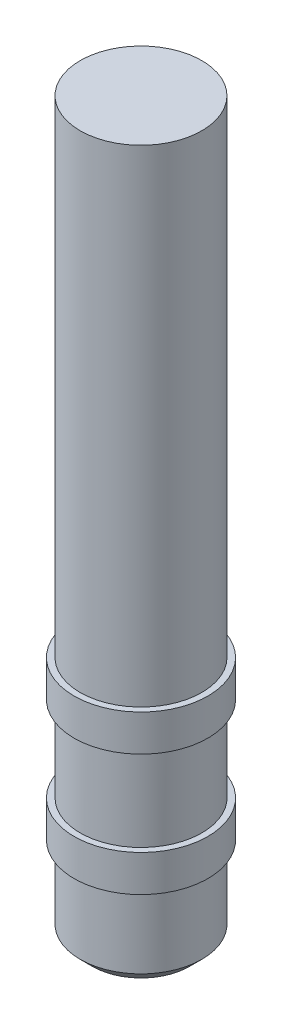
SolidWorks part; units mm, degrees
ref_plane "Front Plane" through (0, 0, 0) normal (0, 0, 1) x (1, 0, 0)
ref_plane "Top Plane" through (0, 0, 0) normal (0, 1, 0) x (1, 0, 0)
ref_plane "Right Plane" through (0, 0, 0) normal (1, 0, 0) x (0, 0, -1)
sketch "Sketch1" plane through (0, 0, 0) normal (0, 1, 0) x (1, 0, 0)
  circle A0 centre (0, 0) radius 5
  dimension "D1" = 10
extrude "Boss-Extrude1" add sketch "Sketch1" along normal blind 60
sketch "Sketch2" plane through (0, 60, 0) normal (0, 1, 0) x (1, 0, 0)
  circle A0 centre (0, 0) radius 5.5
  dimension "D1" = 11
extrude "Boss-Extrude2" add sketch "Sketch2" along normal blind 3 from offset 43 offset against normal yes
chamfer "Chamfer1" distance 1 angle 45 1 edges at (0, 0, 5)
sketch "Sketch3" plane through (0, 0, 0) normal (0, -1, 0) x (1, 0, 0)
  circle A0 centre (0, 0) radius 5.5
  dimension "D1" = 11
extrude "Boss-Extrude3" add sketch "Sketch3" along normal blind 3 from offset 10 offset against normal yes
